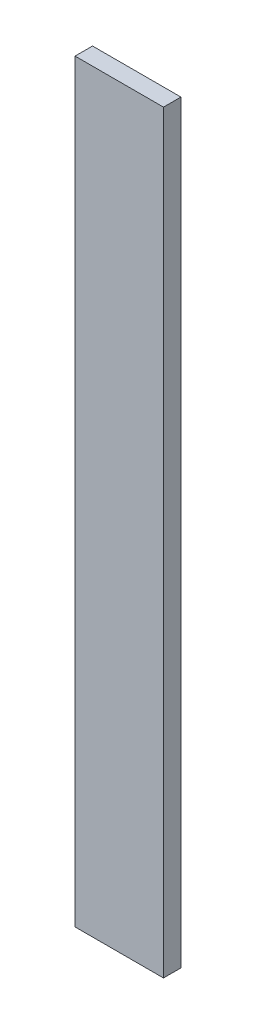
SolidWorks part; units mm, degrees
ref_plane "Front Plane" through (0, 0, 0) normal (0, 0, 1) x (1, 0, 0)
ref_plane "Top Plane" through (0, 0, 0) normal (0, 1, 0) x (1, 0, 0)
ref_plane "Right Plane" through (0, 0, 0) normal (1, 0, 0) x (0, 0, -1)
sketch "Sketch1" plane through (0, 0, 0) normal (0, 0, 1) x (1, 0, 0)
  line L0 (1731.5295, 2770.3511) -> (1731.5295, 1946.9847)
  line L1 (1731.5295, 1946.9847) -> (1828.0495, 1946.9847)
  line L2 (1828.0495, 1946.9847) -> (1828.0495, 2770.3511)
  line L3 (1828.0495, 2770.3511) -> (1731.5295, 2770.3511)
extrude "Boss-Extrude1" add sketch "Sketch1" along normal blind 19.05
